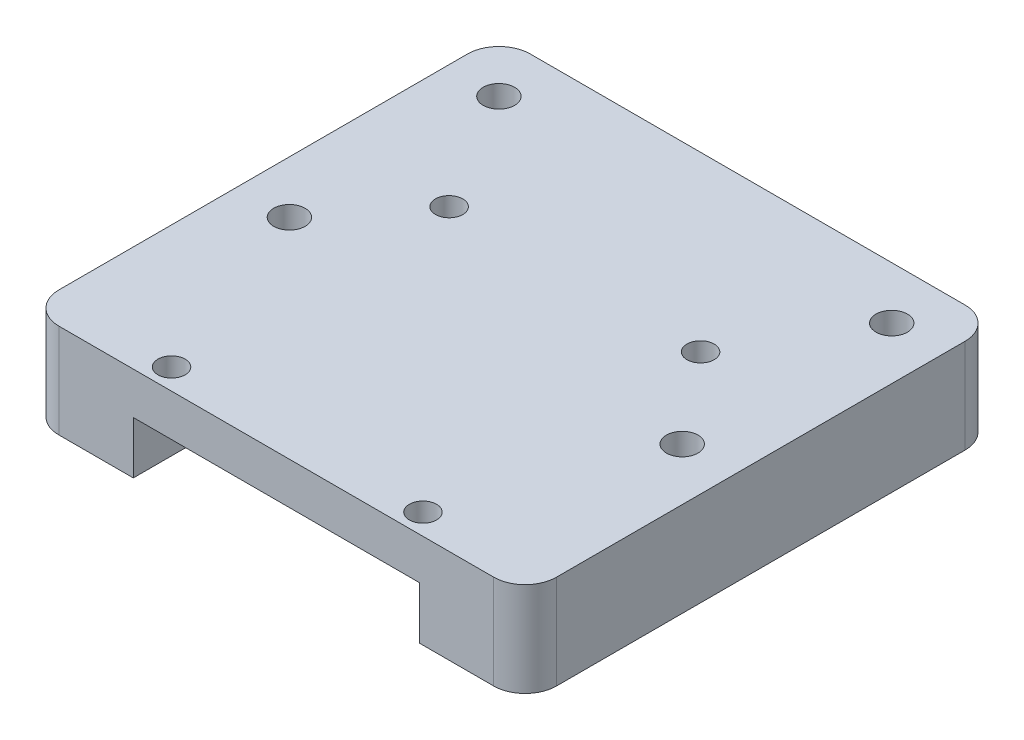
SolidWorks part; units mm, degrees
ref_plane "前视基准面" through (0, 0, 0) normal (0, 0, 1) x (1, 0, 0)
ref_plane "上视基准面" through (0, 0, 0) normal (0, 1, 0) x (1, 0, 0)
ref_plane "右视基准面" through (0, 0, 0) normal (1, 0, 0) x (0, 0, -1)
other "Configuration Table"
sketch "草图1" plane through (0, 0, 0) normal (0, 1, 0) x (1, 0, 0)
  line L0 (0, 22.5) -> (0, 0) construction
  line L1 (-23.75, 22.5) -> (23.75, 22.5)
  line L2 (-23.75, 22.5) -> (-23.75, -22.5)
  line L3 (-23.75, -22.5) -> (23.75, -22.5)
  line L4 (23.75, 22.5) -> (23.75, -22.5)
  line L5 (-23.75, 22.5) -> (23.75, -22.5) construction
  line L6 (-23.75, -22.5) -> (23.75, 22.5) construction
  line L8 (-14, 13.5) -> (14, 13.5) construction
  line L9 (-14, 13.5) -> (-14, -22.5) construction
  line L10 (-14, -22.5) -> (14, -22.5) construction
  line L11 (14, 13.5) -> (14, -22.5) construction
  line L12 (-14, 13.5) -> (14, -22.5) construction
  line L13 (-14, -22.5) -> (14, 13.5) construction
  circle A0 centre (-18.75, 17.5) radius 1.5
  circle A1 centre (-18.75, -2.5) radius 1.5
  circle A2 centre (18.75, -2.5) radius 1.5
  circle A3 centre (18.75, 17.5) radius 1.5
  circle A4 centre (-12, -20.5) radius 1.3
  circle A6 centre (-12, 6) radius 1.3
  circle A7 centre (12, 6) radius 1.3
  circle A8 centre (12, -20.5) radius 1.3
  point P0 (0, 0)
  point P16 (0, -4.5)
  dimension "D3" = 5
  dimension "D4" = 3
  dimension "D5" = 3
  dimension "D9" = 2
  dimension "D11" = 2.6
  dimension "D12" = 2.6
  dimension "D1" = 45
  dimension "D2" = 47.5
  dimension "D6" = 5
  dimension "D7" = 36
  dimension "D8" = 28
  dimension "D10" = 2
  dimension "D13" = 26.5
  dimension "D14" = 5
  dimension "D15" = 20
extrude "凸台-拉伸1" add sketch "草图1" along normal blind 9
sketch "草图2" plane through (0, 0, 0) normal (0, -1, 0) x (1, 0, 0)
  line L0 (-23.75, 22.5) -> (23.75, 22.5) construction
  line L1 (-13.65, -13.5) -> (13.65, -13.5)
  line L2 (-13.65, -13.5) -> (-13.65, 22.5)
  line L3 (-13.65, 22.5) -> (13.65, 22.5)
  line L4 (13.65, -13.5) -> (13.65, 22.5)
  line L5 (-13.65, -13.5) -> (13.65, 22.5) construction
  line L6 (-13.65, 22.5) -> (13.65, -13.5) construction
  point P0 (0, 4.5)
  dimension "D1" = 36
  dimension "D2" = 27.3
extrude "切除-拉伸1" cut sketch "草图2" against normal blind 5
fillet "圆角1" radius 3 4 edges at (23.75, 4.5, 22.5) (23.75, 4.5, -22.5) (-23.75, 4.5, -22.5) (-23.75, 4.5, 22.5)
